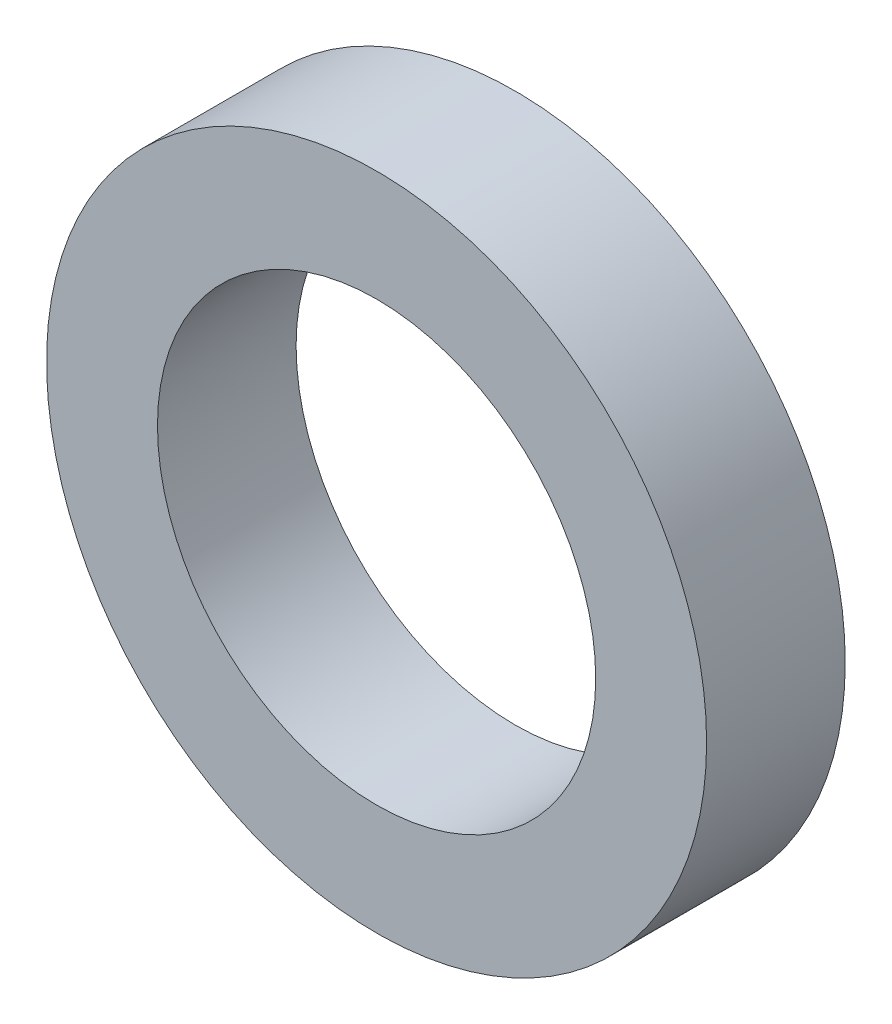
SolidWorks part; units mm, degrees
ref_plane "Спереди" through (0, 0, 0) normal (0, 0, 1) x (1, 0, 0)
ref_plane "Сверху" through (0, 0, 0) normal (0, 1, 0) x (1, 0, 0)
ref_plane "Справа" through (0, 0, 0) normal (1, 0, 0) x (0, 0, -1)
sketch "Эскиз1" plane through (0, 0, 0) normal (0, 0, 1) x (1, 0, 0)
  circle A0 centre (0, 0) radius 7.903
  circle A2 centre (0, 0) radius 11.903
  dimension "D1" = 15.806
  dimension "D2" = 4
extrude "Бобышка-Вытянуть1" add sketch "Эскиз1" along normal blind 5
